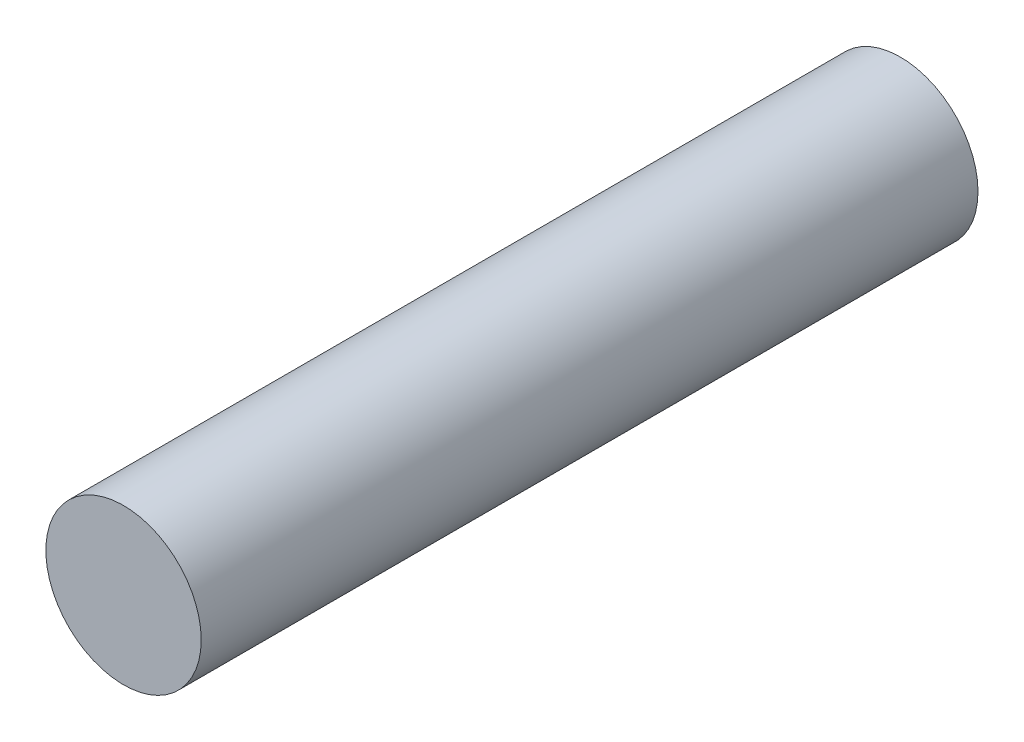
SolidWorks part; units mm, degrees
ref_plane "前视基准面" through (0, 0, 0) normal (0, 0, 1) x (1, 0, 0)
ref_plane "上视基准面" through (0, 0, 0) normal (0, 1, 0) x (1, 0, 0)
ref_plane "右视基准面" through (0, 0, 0) normal (1, 0, 0) x (0, 0, -1)
other "Configuration Table"
sketch "草图1" plane through (0, 0, 0) normal (0, 0, 1) x (1, 0, 0)
  circle A0 centre (0, 0) radius 1
extrude "凸台-拉伸2" add sketch "草图1" along normal blind 10
